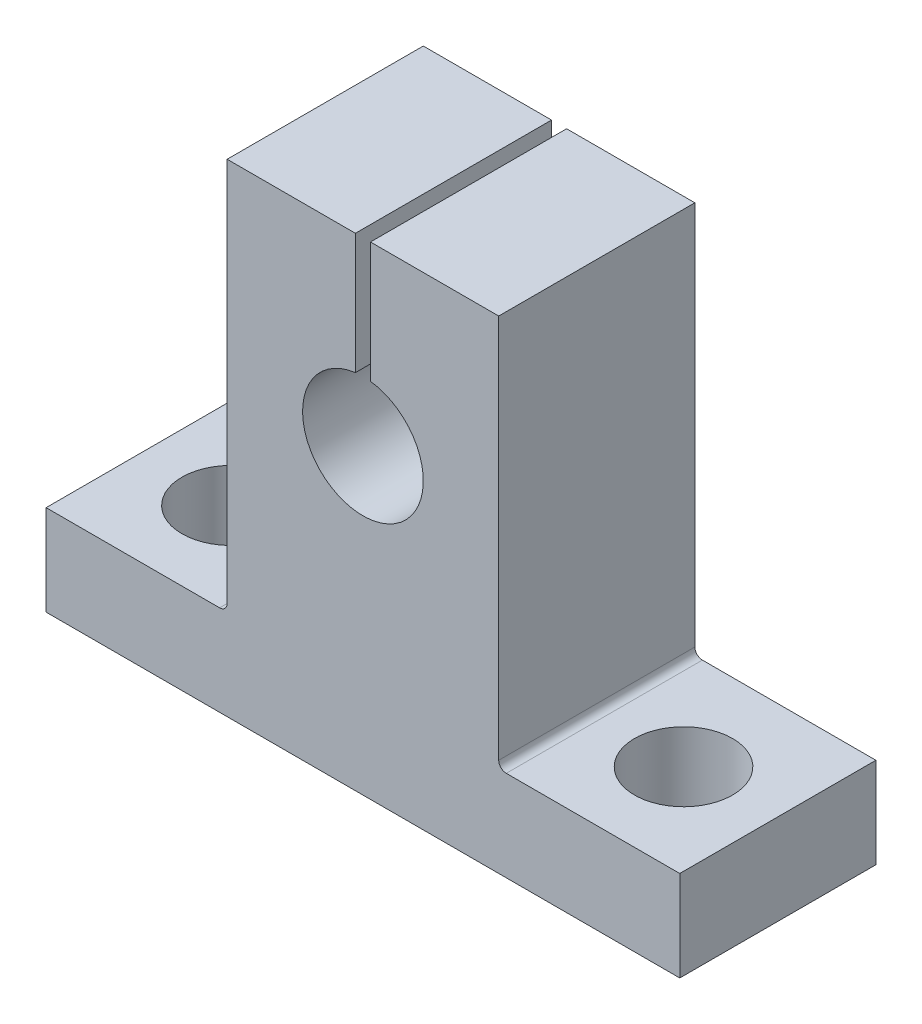
SolidWorks part; units mm, degrees
ref_plane "Front Plane" through (0, 0, 0) normal (0, 0, 1) x (1, 0, 0)
ref_plane "Top Plane" through (0, 0, 0) normal (0, 1, 0) x (1, 0, 0)
ref_plane "Right Plane" through (0, 0, 0) normal (1, 0, 0) x (0, 0, -1)
ref_plane "Plane1" through (0, 0, 0) normal (0, 0, -1) x (-1, 0, 0)
sketch "Sketch1" plane through (0, 0, 0) normal (0, 0, -1) x (-1, 0, 0)
  line L0 (21.2857, 10.5) -> (-20.7143, 10.5)
  line L1 (-20.7143, 10.5) -> (-20.7143, -21.5)
  line L2 (-20.7143, -21.5) -> (21.2857, -21.5)
  line L3 (21.2857, -21.5) -> (21.2857, 10.5)
extrude "Boss-Extrude1" add sketch "Sketch1" against normal blind 13
sketch "Sketch2" plane through (0, 0, 13) normal (0, 0, 1) x (1, 0, 0)
  line L0 (8.7143, 10.5) -> (8.7143, -15.5)
  line L1 (8.7143, -15.5) -> (20.7143, -15.5)
  line L2 (20.7143, -15.5) -> (20.7143, 10.5)
  line L3 (20.7143, 10.5) -> (8.7143, 10.5)
extrude "Cut-Extrude1" cut sketch "Sketch2" against normal through all
sketch "Sketch3" plane through (0, 0, 13) normal (0, 0, 1) x (1, 0, 0)
  line L0 (-21.2857, -15.5) -> (-9.2857, -15.5)
  line L1 (-9.2857, -15.5) -> (-9.2857, 10.5)
  line L2 (-9.2857, 10.5) -> (-21.2857, 10.5)
  line L3 (-21.2857, 10.5) -> (-21.2857, -15.5)
extrude "Cut-Extrude2" cut sketch "Sketch3" against normal through all
sketch "Sketch4" plane through (0, 0, 13) normal (0, 0, 1) x (1, 0, 0)
  line L0 (0.2143, 10.5) -> (-0.7857, 10.5)
  line L1 (-0.7857, 10.5) -> (-0.7857, 2.5)
  line L2 (0.2143, 2.5) -> (0.2143, 10.5)
  arc A0 (-0.7857, 2.5) -> (0.2143, 2.5) centre (-0.2857, -1.4686) cw
extrude "Cut-Extrude3" cut sketch "Sketch4" against normal through all
ref_plane "Plane2" through (0, -1.4686, 0) normal (0, 1, 0) x (1, 0, 0)
sketch "Sketch5" plane through (0, -1.4686, 0) normal (0, 1, 0) x (1, 0, 0)
  line L0 (3.7143, 0) -> (-0.2857, 0)
  line L1 (-0.2857, 0) -> (-0.2857, -13)
  line L2 (-0.2857, -13) -> (3.7143, -13)
  line L3 (3.7143, -13) -> (3.7143, 0)
  line L4 (-0.2857, 0) -> (-0.2857, -13) construction
revolve "Cut-Revolve1" cut sketch "Sketch5" angle 360 about L4
hole_wizard "Ø6.5 (6.5) Diameter Hole1" positions "Sketch7" profile "Sketch6" hole size "Ø6.5" standard "ANSI Metric"
sketch "Sketch7" plane through (0, -21.5, 0) normal (0, -1, 0) x (-1, 0, 0)
  point P0 (-14.7143, -6.7494)
sketch "Sketch6" plane through (14.7143, -21.5, 6.7494) normal (1, 0, 0) x (0, 0, -1)
  line L0 (0, 0) -> (0, 32)
  line L1 (0, 32) -> (3.25, 32)
  line L2 (3.25, 32) -> (3.25, 0)
  line L5 (3.25, 0) -> (0, 0)
  line L11 (0, -6.35) -> (0, 107.95) construction
  dimension "Thru Hole Dia." = 6.5
  dimension "Thru Hole Depth" = 32
hole_wizard "Ø6.5 (6.5) Diameter Hole2" positions "Sketch9" profile "Sketch8" hole size "Ø6.5" standard "ANSI Metric"
sketch "Sketch9" plane through (0, -15.5, 0) normal (0, 1, 0) x (1, 0, 0)
  point P0 (-15.2857, -6.7494)
sketch "Sketch8" plane through (-15.2857, -15.5, 6.7494) normal (1, 0, 0) x (0, 0, 1)
  line L0 (0, 0) -> (0, 6)
  line L1 (0, 6) -> (3.25, 6)
  line L2 (3.25, 6) -> (3.25, 0)
  line L5 (3.25, 0) -> (0, 0)
  line L11 (0, -6.35) -> (0, 107.95) construction
  dimension "Thru Hole Dia." = 6.5
  dimension "Thru Hole Depth" = 6
fillet "Fillet1" radius 0.5 2 edges at (8.7143, -15.5, 6.5) (-9.2857, -15.5, 6.5)
